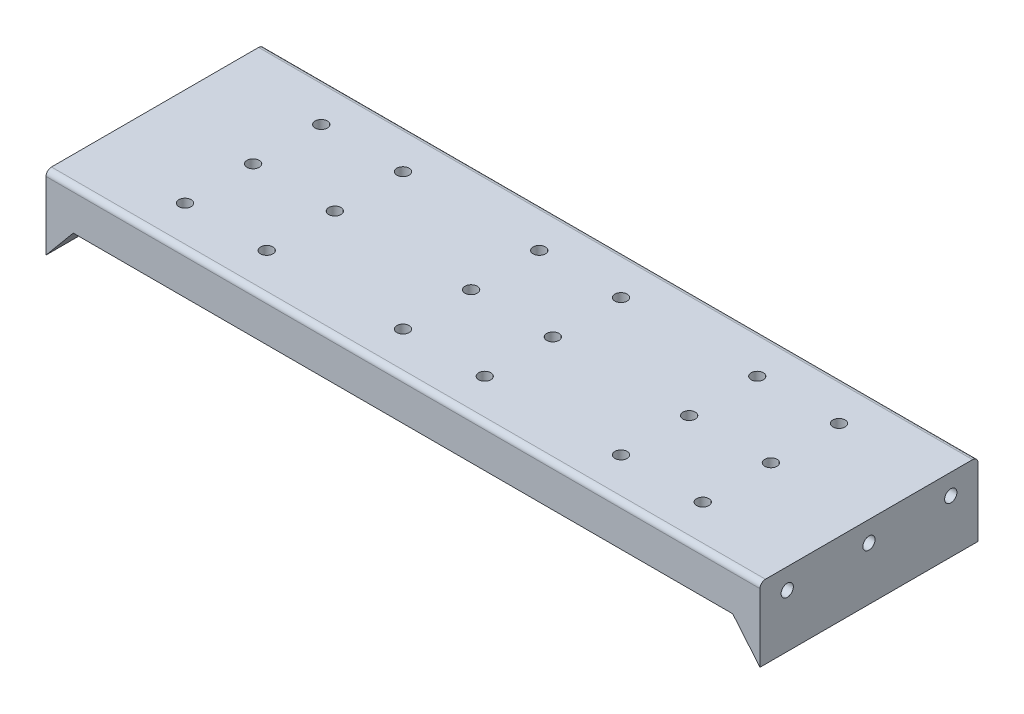
SolidWorks part; units mm, degrees
ref_plane "Front Plane" through (0, 0, 0) normal (0, 0, 1) x (1, 0, 0)
ref_plane "Top Plane" through (0, 0, 0) normal (0, 1, 0) x (1, 0, 0)
ref_plane "Right Plane" through (0, 0, 0) normal (1, 0, 0) x (0, 0, -1)
sketch "Sketch1" plane through (0, 0, 0) normal (0, 1, 0) x (1, 0, 0)
  line L1 (-131, 40) -> (131, 40)
  line L2 (-131, 40) -> (-131, -40)
  line L3 (-131, -40) -> (131, -40)
  line L4 (131, 40) -> (131, -40)
  line L5 (-131, 40) -> (131, -40) construction
  line L6 (-131, -40) -> (131, 40) construction
  point P0 (0, 0)
  dimension "D1" = 80
  dimension "D2" = 262
extrude "Boss-Extrude1" add sketch "Sketch1" along normal blind 15
sketch "Sketch2" plane through (-131, 0, 0) normal (-1, 0, 0) x (0, 0, 1)
  line L0 (-40, 7.5) -> (40, 7.5) construction
  line L1 (-40, 15) -> (-40, 0) construction
  line L2 (40, 15) -> (40, 0) construction
  line L3 (0, 0) -> (0, 15) construction
  line L4 (-40, 15) -> (40, 15) construction
  circle A0 centre (0, 7.5) radius 2.25
  circle A1 centre (-30, 7.5) radius 2.25
  circle A2 centre (30, 7.5) radius 2.25
  dimension "D1" = 4.5
  dimension "D2" = 4.5
  dimension "D3" = 30
extrude "Cut-Extrude1" cut sketch "Sketch2" against normal blind 40
ref_plane "Plane1" through (-121, 0, 0) normal (-1, 0, 0) x (0, 0, 1)
sketch "Sketch3" plane through (-121, 0, 0) normal (-1, 0, 0) x (0, 0, 1)
  line L0 (-33.75, 5.3349) -> (-33.75, 0)
  line L1 (0, 11.8301) -> (-3.75, 9.6651)
  line L2 (-3.75, 9.6651) -> (-3.75, 5.3349)
  line L5 (3.75, 5.3349) -> (3.75, 9.6651)
  line L6 (3.75, 9.6651) -> (0, 11.8301)
  line L7 (-30, 11.8301) -> (-33.75, 9.6651)
  line L8 (-33.75, 9.6651) -> (-33.75, 5.3349)
  line L11 (-26.25, 5.3349) -> (-26.25, 9.6651)
  line L12 (-26.25, 9.6651) -> (-30, 11.8301)
  line L13 (-40, 0) -> (40, 0) construction
  line L15 (-3.75, 5.3349) -> (-3.75, 0)
  line L16 (3.75, 5.3349) -> (3.75, 0)
  line L17 (-33.75, 0) -> (-26.25, 0)
  line L18 (-28.125, 4.2524) -> (-26.25, 5.3349) [skipped]
  line L19 (-33.75, 5.3349) -> (-31.875, 4.2524) [skipped]
  line L20 (-1.875, 4.2524) -> (0, 3.1699) [skipped]
  line L21 (1.875, 4.2524) -> (3.75, 5.3349) [skipped]
  line L22 (-3.75, 0) -> (3.75, 0)
  line L23 (0, 0) -> (0, 15) construction
  line L24 (-40, 15) -> (40, 15) construction
  line L25 (33.75, 5.3349) -> (33.75, 0)
  line L26 (33.75, 9.6651) -> (33.75, 5.3349)
  line L27 (30, 11.8301) -> (33.75, 9.6651)
  line L28 (26.25, 9.6651) -> (30, 11.8301)
  line L29 (26.25, 5.3349) -> (26.25, 9.6651)
  line L30 (26.25, 5.3349) -> (26.25, 0)
  line L31 (33.75, 0) -> (26.25, 0)
  line L32 (-26.25, 5.3349) -> (-26.25, 0)
  circle A0 centre (0, 7.5) radius 3.75 construction
  circle A1 centre (-30, 7.5) radius 3.75 construction
  dimension "D1" = 7.5
  dimension "D2" = 7.5
extrude "Cut-Extrude2" cut sketch "Sketch3" against normal blind 3.2
mirror "Mirror1" about plane through (0, 0, 0) normal (1, 0, 0) of "Cut-Extrude1", "Cut-Extrude2"
sketch "Sketch4" plane through (0, 15, 0) normal (0, 1, 0) x (1, 0, 0)
  line L0 (-131, 0) -> (131, 0) construction
  line L1 (-131, 40) -> (-131, -40) construction
  line L2 (131, -40) -> (131, 40) construction
  line L3 (0, 40) -> (0, -40) construction
  line L4 (131, 40) -> (-131, 40) construction
  line L5 (-131, -40) -> (131, -40) construction
  line L6 (-15, 40) -> (-15, -40) construction
  circle A0 centre (-15, 0) radius 2.25
  circle A1 centre (-15, 25) radius 2.25
  circle A2 centre (-15, -25) radius 2.25
  circle A3 centre (15, -25) radius 2.25
  circle A4 centre (15, 0) radius 2.25
  circle A5 centre (15, 25) radius 2.25
  dimension "D1" = 4.5
  dimension "D2" = 4.5
  dimension "D3" = 50
  dimension "D4" = 30
extrude "Cut-Extrude3" cut sketch "Sketch4" against normal through all
pattern_linear "LPattern1" count 2 spacing 80 along (1, 0, 0) count 2 spacing 80 along (-1, 0, 0) of "Cut-Extrude3"
fillet "Fillet1" radius 2 2 edges at (0, 15, -40) (0, 15, 40)
sketch "Sketch7" plane through (0, 0, 40) normal (0, 0, 1) x (1, 0, 0)
  line L0 (-131, 0) -> (-131, -12)
  line L1 (-131, -12) -> (-121, 0)
  line L2 (-121, 0) -> (-131, 0)
  line L3 (-131, 0) -> (131, 0) construction
  dimension "D1" = 12
  dimension "D2" = 10
extrude "Boss-Extrude2" add sketch "Sketch7" against normal through all
mirror "Mirror2" about plane through (0, 0, 0) normal (1, 0, 0) of "Boss-Extrude2"
